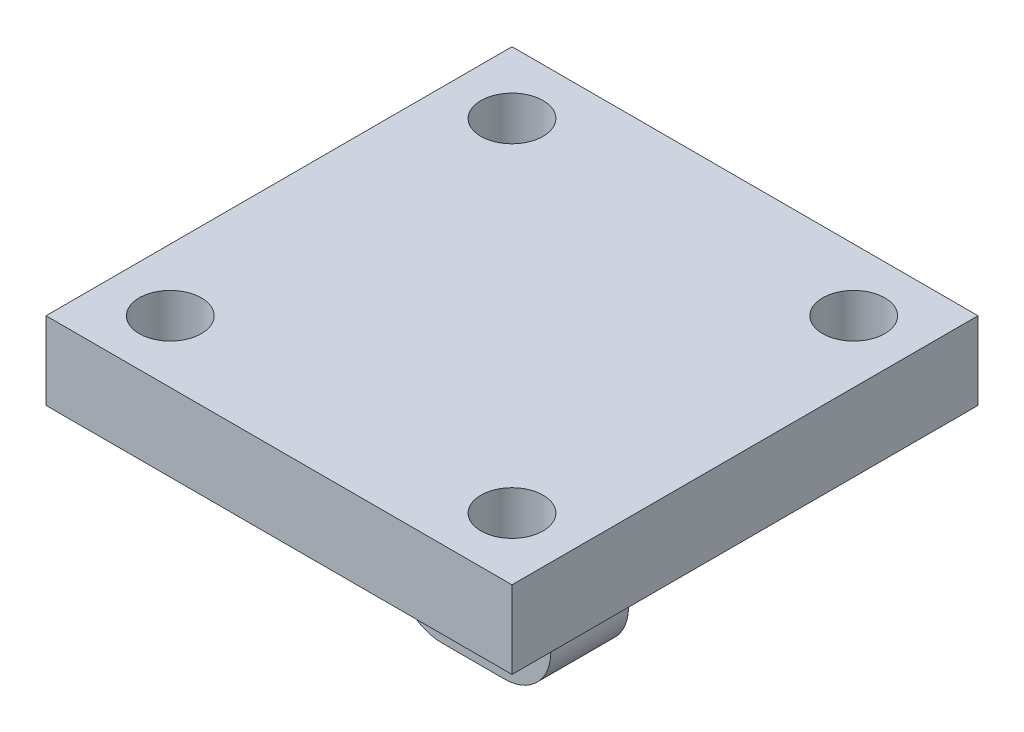
SolidWorks part; units mm, degrees
ref_plane "Front" through (0, 0, 0) normal (0, 0, 1) x (1, 0, 0)
ref_plane "Top" through (0, 0, 0) normal (0, 1, 0) x (1, 0, 0)
ref_plane "Right" through (0, 0, 0) normal (1, 0, 0) x (0, 0, -1)
sketch "Sketch2" plane through (0, 0, 0) normal (0, 0, 1) x (1, 0, 0)
  line L0 (-5, 4.24) -> (-10, 4.24) construction
  line L1 (0, 0) -> (-10, 0)
  line L2 (0, 0) -> (0, 18)
  line L3 (0, 18) -> (-10, 18)
  line L4 (-10, 0) -> (-10, 18)
  line L5 (-5, 4.24) -> (0, 4.24) construction
  circle A0 centre (-5, 4.24) radius 2
  dimension "D4" = 4
  dimension "D1" = 18
  dimension "D2" = 10
  dimension "D3" = 13.76
extrude "Boss-Extrude1" add sketch "Sketch2" along normal blind 5 contours L4 L1 L2 L3 A0
sketch "Sketch3" plane through (0, 18, 0) normal (0, 1, 0) x (1, 0, 0)
  line L1 (-20, -17.5) -> (10, -17.5)
  line L2 (-20, -17.5) -> (-20, 12.5)
  line L3 (-20, 12.5) -> (10, 12.5)
  line L4 (10, -17.5) -> (10, 12.5)
  line L7 (0, 0) -> (10, 0) construction
  line L8 (-10, 0) -> (-20, 0) construction
  line L9 (0, 0) -> (0, 12.5) construction
  line L10 (0, -5) -> (0, -17.5) construction
  dimension "D1" = 30
  dimension "D2" = 30
extrude "Boss-Extrude2" add sketch "Sketch3" against normal blind 5
fillet "Fillet1" radius 5 2 edges at (-10, 13, 2.5) (0, 13, 2.5)
fillet "Fillet2" radius 3 2 edges at (0, 0, 2.5) (-10, 0, 2.5)
sketch "Sketch4" plane through (0, 18, 0) normal (0, 1, 0) x (1, 0, 0)
  line L0 (10, -17.5) -> (10, 12.5) construction
  line L1 (10, 12.5) -> (-20, 12.5) construction
  line L2 (-20, 12.5) -> (-20, -17.5) construction
  line L3 (-20, -17.5) -> (10, -17.5) construction
  circle A0 centre (-16, 8.5) radius 2
  circle A1 centre (6, 8.5) radius 2
  circle A2 centre (6, -13.5) radius 2
  circle A3 centre (-16, -13.5) radius 2
  dimension "D1" = 4
  dimension "D2" = 4
  dimension "D3" = 4
  dimension "D4" = 4
  dimension "D5" = 4
  dimension "D6" = 4
  dimension "D7" = 4
  dimension "D8" = 4
  dimension "D9" = 4
  dimension "D10" = 4
  dimension "D11" = 4
  dimension "D12" = 4
extrude "Cut-Extrude1" cut sketch "Sketch4" against normal blind 5
